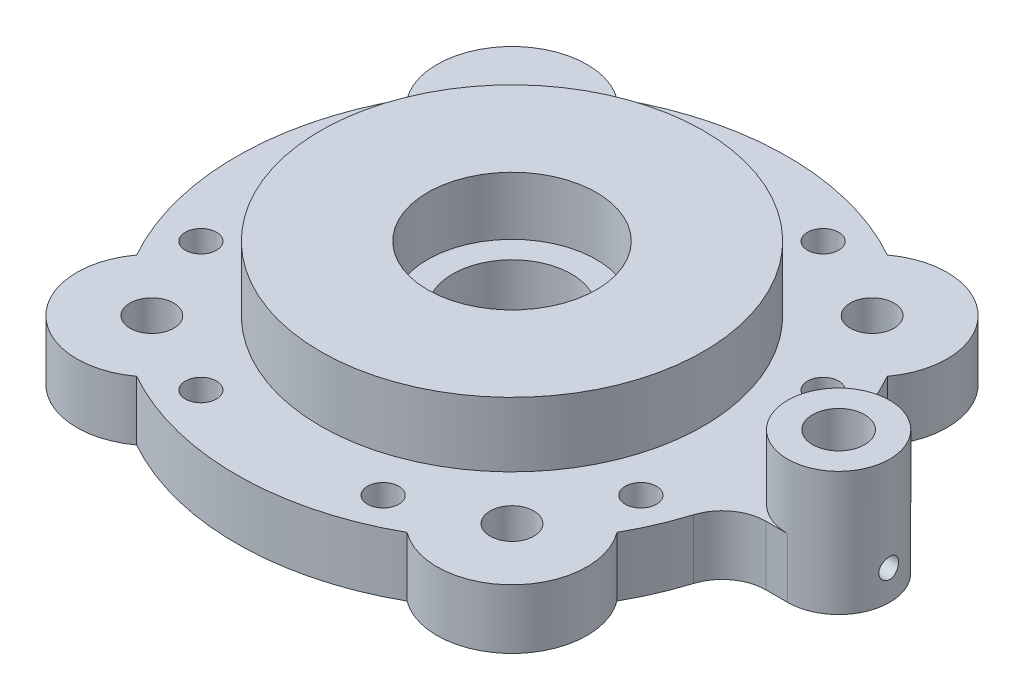
SolidWorks part; units mm, degrees
material "1060 Alloy"
ref_plane "Front" through (0, 0, 0) normal (0, 0, 1) x (1, 0, 0)
ref_plane "Top" through (0, 0, 0) normal (0, 1, 0) x (1, 0, 0)
ref_plane "Right" through (0, 0, 0) normal (1, 0, 0) x (0, 0, -1)
sketch "Sketch1" plane through (0, 0, 0) normal (0, 1, 0) x (1, 0, 0)
  line L0 (44.1, 0) -> (52.2672, 0) construction
  line L1 (48.7972, 8.1672) -> (52.2672, 8.1672)
  line L2 (48.7972, -8.1672) -> (52.2672, -8.1672)
  line L3 (44.1, 0) -> (60.4344, 0) construction
  arc A0 (42.1126, 13.0895) -> (42.1126, -13.0895) centre (0, 0) ccw
  circle A1 centre (0, 0) radius 44.1 construction
  arc A2 (52.2672, -8.1672) -> (52.2672, 8.1672) centre (52.2672, 0) ccw
  arc A3 (42.1126, 13.0895) -> (48.7972, 8.1672) centre (48.7972, 15.1672) ccw
  arc A4 (48.7972, -8.1672) -> (42.1126, -13.0895) centre (48.7972, -15.1672) ccw
  point P5 (34.5422, 0)
  point P10 (43.3371, 8.1672)
  dimension "D1" = 88.2
  dimension "D4" = 7
  dimension "D2" = 16.3344
  dimension "D3" = 16.3344
extrude "base" add sketch "Sketch1" along normal blind 9.525
sketch "Sketch2" plane through (0, 9.525, 0) normal (0, 1, 0) x (1, 0, 0)
  line L0 (52.2672, 8.1672) -> (52.2672, -8.1672) construction
  circle A0 centre (0, 0) radius 30.6267
  arc A1 (52.2672, -8.1672) -> (52.2672, 8.1672) centre (52.2672, 0) ccw construction
  circle A2 centre (52.2672, 0) radius 8.1672
  circle A3 centre (52.2672, 0) radius 4.1672
  dimension "D1" = 61.2534
  dimension "D2" = 8.3344
sketch "Sketch3" plane through (0, 0, 0) normal (0, -1, 0) x (1, 0, 0)
  line L0 (0, 0) -> (60.4344, 0) construction
  line L1 (0, 0) -> (31.1834, -31.1834) construction
  circle A0 centre (0, 0) radius 40.75 construction
  circle A1 centre (-28.8146, -28.8146) radius 3.5
  circle A2 centre (-28.8146, 28.8146) radius 3.5
  circle A3 centre (28.8146, 28.8146) radius 3.5
  circle A4 centre (28.8146, -28.8146) radius 3.5
  arc A5 (52.2672, -8.1672) -> (52.2672, 8.1672) centre (52.2672, 0) ccw construction
  arc A6 (42.1126, 13.0895) -> (42.1126, -13.0895) centre (0, 0) ccw construction
  point P14 (0, 0)
  dimension "D1" = 81.5
  dimension "D2" = 7
  dimension "D4" = 45
  dimension "D3" = 4
extrude "square bolt holes" cut sketch "Sketch3" against normal through all and the other way through all
sketch "Sketch11" plane through (0, 0, 0) normal (0, -1, 0) x (1, 0, 0)
  circle A0 centre (-28.8146, 28.8146) radius 12
  circle A1 centre (-28.8146, 28.8146) radius 3.5
  arc A2 (-31.9201, 30.4289) -> (-30.4289, 31.9201) centre (-28.8146, 28.8146) ccw construction
  circle A3 centre (28.8146, 28.8146) radius 3.5
  circle A4 centre (28.8146, 28.8146) radius 12
  circle A5 centre (28.8146, -28.8146) radius 3.5
  circle A6 centre (28.8146, -28.8146) radius 12
  circle A7 centre (-28.8146, -28.8146) radius 3.5
  circle A8 centre (-28.8146, -28.8146) radius 12
  point P19 (0, 0)
  dimension "D1" = 24
  dimension "D2" = 4
extrude "Boss-Extrude1" add sketch "Sketch11" against normal blind 9.525
sketch "Sketch4" plane through (0, 9.525, 0) normal (0, 1, 0) x (1, 0, 0)
  line L0 (0, 0) -> (0, 38.1) construction
  line L1 (0, 38.1) -> (0, 0) construction
  line L2 (0, 0) -> (14.5802, 35.1998) construction
  circle A0 centre (0, 0) radius 38.1 construction
  circle A1 centre (14.5802, 35.1998) radius 2.5
  dimension "D1" = 76.2
  dimension "D3" = 5
  dimension "D2" = 22.5
extrude "housing bolts" cut sketch "Sketch4" against normal blind 44.33
pattern_circular "CirPattern1" count 8 over 360 about axis through (0, 0, 0) along (0, 1, 0) of "housing bolts"
extrude "impeller cavity riser" add sketch "Sketch2" along normal blind 10.3296
sketch "Sketch5" plane through (0, 19.8545, 0) normal (0, 1, 0) x (1, 0, 0)
  circle A0 centre (0, 0) radius 13.5
  dimension "D1" = 27
extrude "seal bore" cut sketch "Sketch5" against normal blind 9.3
sketch "Sketch6" plane through (0, 10.5545, 0) normal (0, 1, 0) x (1, 0, 0)
  circle A0 centre (0, 0) radius 9.5
  dimension "D1" = 19
extrude "bore" cut sketch "Sketch6" against normal blind 39.3
sketch "pressure tap plane alignment" plane through (0, 0, 0) normal (0, -1, 0) x (1, 0, 0)
  line L1 (0, 0) -> (44.1, 0) construction
  line L2 (44.1, 0) -> (44.1, 44.1) construction
  line L3 (44.1, 44.1) -> (0, 44.1) construction
  circle A0 centre (0, 0) radius 44.1 construction
  circle A1 centre (0, 0) radius 44.1 construction
ref_plane "pressure tap plane" through (44.1, 0, 0) normal (1, 0, 0) x (0, 0, -1)
sketch "Sketch9" plane through (44.1, 0, 0) normal (1, 0, 0) x (0, 0, -1)
  line L0 (0, 0) -> (0, 9.525) construction
  line L1 (44.1, 9.525) -> (-44.1, 9.525) construction
  circle A0 centre (0, 4.7625) radius 1.5875
  dimension "D1" = 3.175
extrude "pressure tap" cut sketch "Sketch9" against normal blind 52.75 and the other way through all
sketch "Sketch10" plane through (0, 9.525, 0) normal (0, 1, 0) x (1, 0, 0)
  circle A0 centre (52.2672, 0) radius 1.5875
  dimension "D1" = 3.175
extrude "pressure tap vertical hole" cut sketch "Sketch10" against normal blind 6.35
equation "\"bearing OD\" = 30mm"
equation "\"bearing ID\"= 10mm"
equation "\"bearing depth\"= 9mm"
equation "\"bearing outer race thickness\"= 1mm"
equation "\"bearing inner race thickness\"= 1mm"
equation "\"bearing bore\" = \"bearing depth\" + 1mm"
equation "\"small seal OD\" = 20mm"
equation "\"small seal ID\"= 8mm"
equation "\"small seal depth\" = 8.3mm"
equation "\"small seal bore\" = \"small seal depth\" + 1mm"
equation "\"big seal OD\" = 27mm"
equation "\"big seal ID\"= 15mm"
equation "\"big seal depth\"= 8.3mm"
equation "\"big seal bore\" = \"big seal depth\" + 1mm"
equation "\"z\" = 8 \t\t'number of blades"
equation "\"de\" = 0.426in \t\t'entrance eye diameter"
equation "\"d2\" = 2.097in \t\t'outer diameter of the impeller "
equation "\"d_exit\" = 0.18in \t'volute throat aka D4"
equation "\"theta\" = 15"
equation "\"b2\" = .071in\t\t\t\t\t\t\t'tip height from disc surface at d2"
equation "\"b1\" = \"b2\" + (\"d2\"/2 - \"de\"/2)*sin(\"theta\")\t\t\t'tip height from disc surface at inlet eye"
equation "\"s\" = ( 1/\"z\")*(3.14*\"de\" - (3.14*(\"de\"^2) / (4*(\"b1\"))))\t'thickness of blades, calculated from area"
equation "\"s_opening\" = (3.14*\"de\" - \"z\"*\"s\")/\"z\"\t\t\t\t'ideal gap between blades, calculated from area"
equation "\"area_eye\"=3.14*(\"de\"^2)/4\t\t\t\t\t'eye area"
equation "\"single_channel_area\"=\"s_opening\"*\"b1\"\t\t\t\t'ideal area between two blades"
equation "\"minimum channel width\" = \"s_opening\"\t\t\t\t\t\t\t'minimum s, set this to a bit size for milling or to s_opening for DMLS"
equation "\"inlet area before cut\" = \"minimum channel width\" * (\"z\") * \"b1\"\t\t\t'if minimum channel width>s_opening, this is larger than area_eye"
equation "\"area to cut\" = \"inlet area before cut\" - \"area_eye\"\t\t\t\t\t'amount of extra area\t\t\t\t\t"
equation "\"height to cut\" = \"area to cut\" / ((\"z\")* \"minimum channel width\")+ .0001in\t\t'the 0.0001 in cut is to avoid errors in model"
equation "\"final impeller center height\" = \"impeller base thickness\" + \"b1\" - \"height to cut\"\t'corrected height so that sum of channel areas equals eye area"
equation "\"impeller upper clearance\"= .5mm"
equation "\"impeller horizontal clearance\"= (\"d2\"*1.15 - \"d2\")/2 \t\t\t\t\t'clearance based on D2-D3 ratio for circular volute, ranges 1.15 to 1.2"
equation "\"impeller bottom clearance\"= .5mm"
equation "\"impeller base thickness\"= 2mm"
equation "\"impeller dowel diameter\" = 2mm"
equation "\"impeller bolt head diameter\" = 7.5mm"
equation "\"impeller bolt head depth\" = 4mm"
equation "\"impeller bolt stop depth\" = 3mm"
equation "\"impeller bolt bore\" = 4mm"
equation "\"impeller shaft bore depth\" = 12mm"
equation "\"impeller shaft bore\" = 8mm"
equation "\"impeller boss depth\" = \"impeller shaft bore depth\"+\"impeller bolt stop depth\"+\"impeller bolt head depth\"-\"impeller base thickness\""
equation "\"impeller boss diameter\" = \"big seal ID\""
equation "\"impeller dowel length\" = 2mm*2 + \"impeller shaft bore\""
equation "\"coupler motor shaft hole ID\"= 8mm"
equation "\"coupler OD\"= 17mm"
equation "\"coupler length\"= 25mm"
equation "\"motor OD\" = 64mm"
equation "\"motor shaft diameter\"= 8mm"
equation "\"motor shaft pride\"= 32mm"
equation "\"motor to bearing plate distance\" = \"motor shaft pride\" + 2mm +\"coupler length\"/2"
equation "\"square plate bolt bore\" = 8mm"
equation "\"square plate bolt head diameter\" = 13.5mm"
equation "\"square plate bolt pattern diameter\"= \"motor OD\" + \"square plate bolt head diameter\" + 4mm"
equation "\"motor mount center bore\"= \"coupler OD\"+ 4mm"
equation "\"motor mount post radius\"= ( 3 * \"square plate bolt bore\" ) / 2"
equation "\"motor mount m4 screw hole diameter\"= 4mm"
equation "\"motor mount m4 head diameter\"= 7.25mm"
equation "\"motor mount m4 head depth\"= 4mm"
equation "\"motor mount m4 pattern diamater\" = 30mm"
equation "\"motor mount plate thickness\"= 8mm + \"motor mount m4 head depth\""
equation "\"bearing plate stop ID\" = \"bearing OD\" - 4mm"
equation "\"bearing plate stop depth\" = 3mm"
equation "\"bearing plate thickness\" = \"bearing bore\" + \"bearing plate stop depth\" + \"shaft bearing stop length\""
equation "\"small seal plate lip depth\" = 2mm"
equation "\"small seal plate lip ID\" = \"small seal OD\" - 3mm"
equation "\"small seal plate thickness\" = \"small seal plate lip depth\" + \"small seal bore\""
equation "\"shaft coupler section diameter\" = 8mm"
equation "\"shaft coupler section length\" = \"motor to bearing plate distance\" - \"motor shaft pride\" - 2mm"
equation "\"shaft bearing section diameter\" = \"bearing ID\""
equation "\"shaft bearing section length\" = \"bearing plate stop depth\" + \"bearing depth\""
equation "\"shaft bearing stop diameter\" = \"bearing ID\" + 4mm"
equation "\"shaft bearing stop length\" = 3mm"
equation "\"shaft small seal section diameter\" = \"small seal ID\""
equation "\"shaft small seal section length\" = \"small seal plate thickness\" + 1mm"
equation "\"big seal plate thickness\" = \"big seal plate pressure hole diameter\"*3"
equation "\"big seal plate riser\" = \"impeller housing thickness\"/2 - \"b2\"/2 - \"impeller base thickness\" - \t\"impeller bottom clearance\"\t\t\t'this offsets the gap under the housing"
equation "\"big seal plate pressure hole diameter\" = .125in\t'this is 1/8 drill "
equation "\"big seal plate pressure tap diameter\" = .328125in \t'this is 21/64 drill for a 1/8 ANPT tap"
equation "\"big seal plate pressure tap grip\" = 4mm\t\t'this is the area around the tap so it doesn't crack"
equation "\"big seal plate pressure tap depth\" = 12"
equation "\"impeller cavity center height\"= \"impeller bottom clearance\" + \"impeller upper clearance\" + \"final impeller center height\""
equation "\"impeller cavity diameter\"= 2 * \"impeller horizontal clearance\" + \"d2\" \t\t\t\t\t\t\t\t\t'called D3 analytically"
equation "\"impeller cavity outer height\"= \"impeller bottom clearance\" + \"impeller upper clearance\" + \"impeller base thickness\" + \"b2\" \t\t'this is height at impeller diameter d2, not at d3"
equation "\"impeller housing thickness\"= \"impeller housing exit threaded diameter\" + 2*\"impeller housing outlet grip\""
equation "\"impeller housing diameter\" = \"square plate bolt pattern diameter\" + 2*\"motor mount post radius\""
equation "\"impeller housing bolt count\" = 8"
equation "\"impeller housing bolt diameter\" = 6mm"
equation "\"impeller housing bolt pattern diameter\" = 3in"
equation "\"impeller housing threaded inlet diameter\" = 0.6875in \t\t'this is the 11/16 drill size for 1/2 npt fitting"
equation "\"impeller housing threaded inlet depth\"= 15mm"
equation "\"impeller housing exit threaded diameter\"= 0.6875in \t\t'this is the 11/16 drill size for 1/2 npt fitting"
equation "\"impeller housing exit threaded depth\"= 18mm"
equation "\"impeller housing diffuser conical angle\"=10"
equation "\"impeller housing diffuser tangent angle\"=5"
equation "\"impeller housing outlet grip\" = 5mm"
equation "\"D1@Sketch1\"=\"impeller housing bolt pattern diameter\"+\"impeller housing bolt diameter\"*2"
equation "\"big seal plate lip ID\" = \"big seal OD\" - 3mm"
equation "\"D1@base\" = \"big seal plate thickness\""
equation "\"D1@Sketch2\"=\"impeller cavity diameter\""
equation "\"D1@Sketch3\"=\"square plate bolt pattern diameter\""
equation "\"D2@Sketch3\"=\"square plate bolt bore\"-1mm"
equation "\"D1@square bolt holes\"=\"big seal plate thickness\" - 2mm"
equation "\"D1@Sketch4\"=\"impeller housing bolt pattern diameter\""
equation "\"D2@Sketch4\"=360/\"impeller housing bolt count\"/2"
equation "\"D3@Sketch4\"=\"impeller housing bolt diameter\"-1mm"
equation "\"D1@CirPattern1\"=\"impeller housing bolt count\""
equation "\"D1@impeller cavity riser\" = \"big seal plate riser\""
equation "\"D1@Sketch5\"=\"big seal OD\""
equation "\"D1@seal bore\" = \"big seal bore\""
equation "\"D1@Sketch6\"=\"big seal ID\"+4mm"
equation "\"D1@Sketch9\"=\"big seal plate pressure hole diameter\""
equation "\"D1@pressure tap\"=\"impeller housing diameter\"/2"
equation "\"de_length\" = 10mm\t'entrance eye consistent length"
equation "\"square plate bolt head depth\" = 8mm"
equation "\"shaft impeller section diameter\" = \"impeller shaft bore\""
equation "\"shaft impeller section length\" = \"big seal plate thickness\" + \"big seal plate riser\" + \"impeller bottom clearance\" + \"impeller base thickness\" - \"impeller bolt head depth\" - \"impeller bolt stop depth\""
equation "\"impeller housing diffuser final diameter\" = .5in"
equation "\"D2@Sketch1\"=\"big seal plate pressure tap diameter\" + \"big seal plate pressure tap grip\"*2"
equation "\"D3@Sketch1\"=\"big seal plate pressure tap diameter\" + \"big seal plate pressure tap grip\"*2"
equation "\"D2@pressure tap\"=\"big seal plate pressure tap diameter\"/2+\"big seal plate pressure tap grip\""
equation "\"D2@Sketch2\"=\"big seal plate pressure tap diameter\""
equation "\"D1@Sketch10\"=\"big seal plate pressure hole diameter\""
equation "\"D1@pressure tap vertical hole\" = \"big seal plate thickness\" / 2 + \"big seal plate pressure hole diameter\" / 2"
equation "\"D1@Sketch11\"=\"motor mount post radius\"*2"
equation "\"D1@Boss-Extrude1\"=\"big seal plate thickness\""
